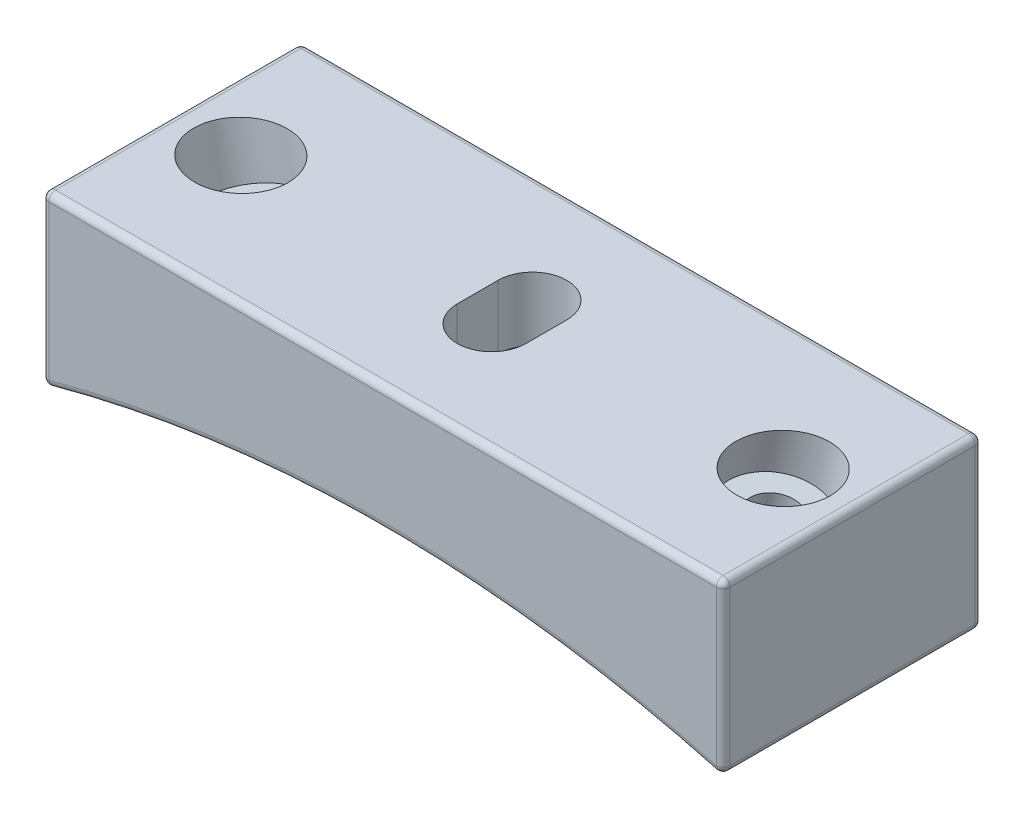
SolidWorks part; units mm, degrees
ref_plane "Front Plane" through (0, 0, 0) normal (0, 0, 1) x (1, 0, 0)
ref_plane "Top Plane" through (0, 0, 0) normal (0, 1, 0) x (1, 0, 0)
ref_plane "Right Plane" through (0, 0, 0) normal (1, 0, 0) x (0, 0, -1)
sketch "Sketch1" plane through (0, 0, 0) normal (0, 0, 1) x (1, 0, 0)
  line L0 (0, 0) -> (0, 21.7025) construction
  line L1 (-31.75, 12.7) -> (31.75, 12.7)
  line L2 (-31.75, 12.7) -> (-31.75, -3.175)
  line L4 (31.75, 12.7) -> (31.75, -3.175)
  line L5 (-31.75, 12.7) -> (31.75, -3.175) construction
  line L6 (-31.75, -3.175) -> (31.75, 12.7) construction
  arc A0 (-31.75, -3.175) -> (31.75, -3.175) centre (0, -117.0694) cw
  point P0 (0, 4.7625)
  point P9 (0, 12.7)
  point P10 (0, 17.0011)
  dimension "D3" = 118.237
  dimension "D1" = 63.5
  dimension "D2" = 15.875
extrude "Boss-Extrude1" add sketch "Sketch1" along normal blind 24.13
ref_plane "Plane2" through (0, 0, 0) normal (1, 0, 0) x (0, 0, -1)
ref_plane "Plane4" through (0, 0, 12.065) normal (0, 0, -1) x (-1, 0, 0)
sketch "Sketch5" plane through (0, 0, 12.065) normal (0, 0, -1) x (-1, 0, 0)
  line L0 (-26.4726, 18.8368) -> (0, -117.0694) construction
  line L1 (-26.6803, 7.947) -> (-17.3136, 9.7715) construction
  line L2 (-22.606, -1.0135) -> (-22.606, 20.8273) construction
  line L3 (0, 7.9238) -> (0, -7.9238) construction
  line L11 (-22.4825, -1.6474) -> (-24.7264, -2.0845)
  line L12 (-24.7264, -2.0845) -> (-26.6803, 7.947)
  line L13 (-26.6803, 7.947) -> (-28.6749, 7.5585)
  line L14 (-28.6749, 7.5585) -> (-30.3613, 16.2166)
  line L15 (-30.3613, 16.2166) -> (-26.123, 17.0421)
  line L16 (-26.123, 17.0421) -> (-22.4825, -1.6474)
  line L17 (-20.1982, 9.2096) -> (-21.8846, 17.8677) construction
  line L18 (-31.75, 12.7) -> (31.75, 12.7) construction
  arc A0 (31.75, -3.175) -> (-31.75, -3.175) centre (0, -117.0694) ccw construction
  point P19 (-20.878, 12.7)
  dimension "D1" = 22.606
  dimension "D2" = 2.286
  dimension "D3" = 4.318
  dimension "D4" = 3.556
revolve "Cut-Revolve1" cut sketch "Sketch5" angle 360 about L0
mirror "Mirror1" about plane through (0, 0, 0) normal (1, 0, 0) of "Cut-Revolve1"
fillet "Fillet1" radius 0.635 12 edges at (0, 12.7, 0) (0, 1.1676, 0) (-31.75, 12.7, 12.065) (-31.75, -3.175, 12.065) (-31.75, 4.7625, 0) (-31.75, 4.7625, 24.13) (0, 12.7, 24.13) (0, 1.1676, 24.13) (31.75, -3.175, 12.065) (31.75, 4.7625, 24.13) (31.75, 12.7, 12.065) (31.75, 4.7625, 0)
sketch "Sketch17" plane through (0, 12.7, 0) normal (0, 1, 0) x (1, 0, 0)
  line L0 (0, -13.97) -> (0, -10.16) construction
  line L1 (0, -7.9238) -> (0, 7.9238) construction
  line L2 (-3.2004, -13.97) -> (-3.2004, -10.16)
  line L3 (3.2004, -13.97) -> (3.2004, -10.16)
  line L4 (7.9238, -12.065) -> (-7.9238, -12.065) construction
  arc A0 (-3.2004, -13.97) -> (3.2004, -13.97) centre (0, -13.97) ccw
  arc A1 (3.2004, -10.16) -> (-3.2004, -10.16) centre (0, -10.16) ccw
  point P5 (0, -12.065)
  dimension "D1" = 3.2004
  dimension "D2" = 1.905
  dimension "D3" = 3.81
extrude "Cut-Extrude1" cut sketch "Sketch17" against normal through all
ref_plane "Plane5" through (0, 1.1676, 0) normal (0, -1, 0) x (-1, 0, 0)
sketch "Sketch18" plane through (0, 1.1676, 0) normal (0, -1, 0) x (-1, 0, 0)
  line L0 (0, -10.16) -> (0, -13.97) construction
  line L1 (8.382, -10.16) -> (8.382, -13.97)
  line L3 (-8.382, -10.16) -> (-8.382, -13.97)
  arc A0 (8.382, -10.16) -> (-8.382, -10.16) centre (0, -10.16) ccw
  arc A1 (-8.382, -13.97) -> (8.382, -13.97) centre (0, -13.97) ccw
  point P2 (0, -12.065)
  dimension "D1" = 8.382
extrude "Cut-Extrude6" cut sketch "Sketch18" against normal blind 5.588 and the other way through all
